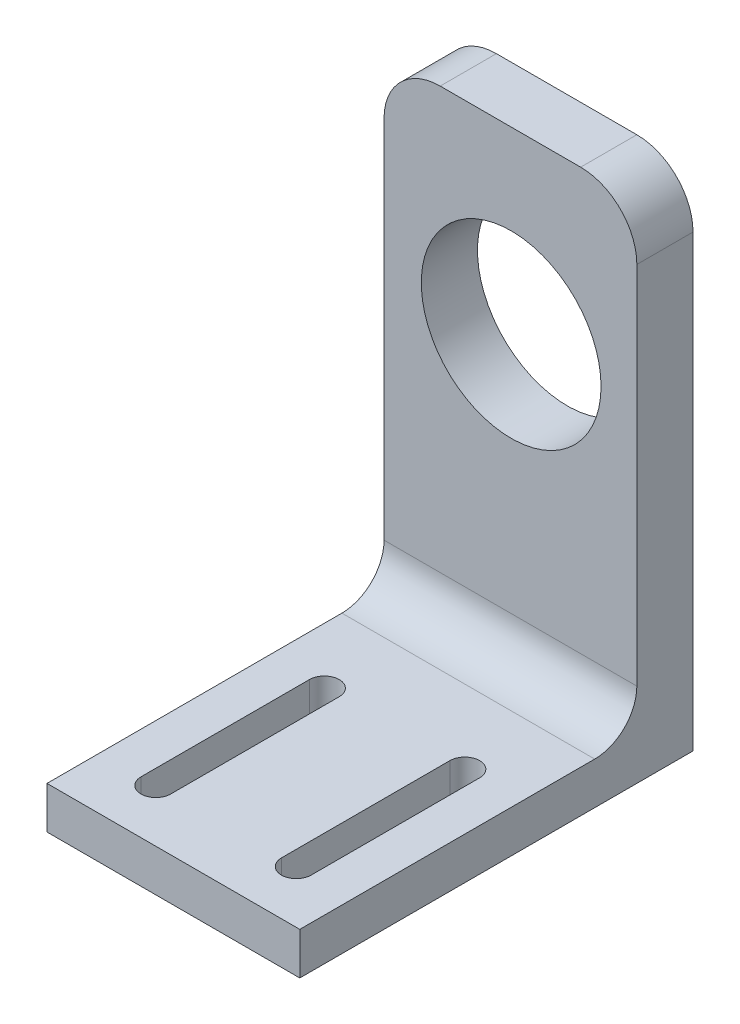
SolidWorks part; units mm, degrees
ref_plane "Front Plane" through (0, 0, 0) normal (0, 0, 1) x (1, 0, 0)
ref_plane "Top Plane" through (0, 0, 0) normal (0, 1, 0) x (1, 0, 0)
ref_plane "Right Plane" through (0, 0, 0) normal (1, 0, 0) x (0, 0, -1)
sketch "Sketch1" plane through (0, 0, 0) normal (0, 0, 1) x (1, 0, 0)
  line L1 (-22.5, 45) -> (22.5, 45)
  line L2 (-22.5, 45) -> (-22.5, -45)
  line L3 (-22.5, -45) -> (22.5, -45)
  line L4 (22.5, 45) -> (22.5, -45)
  line L5 (0, -45) -> (0, 45) construction
  line L6 (-22.5, 0) -> (22.5, 0) construction
  point P0 (0, 0)
  dimension "D1" = 45
  dimension "D2" = 90
extrude "Boss-Extrude1" add sketch "Sketch1" along normal blind 10
sketch "Sketch2" plane through (0, 0, 0) normal (0, 0, 1) x (1, 0, 0)
  circle A0 centre (0.1295, 13.0055) radius 16
extrude "Cut-Extrude1" cut sketch "Sketch2" along normal blind 28
fillet "Fillet1" radius 10 2 edges at (22.5, 45, 5) (-22.5, 45, 5)
sketch "Sketch3" plane through (0, 0, 10) normal (0, 0, 1) x (1, 0, 0)
  line L0 (-22.5, 35) -> (-22.5, -45) construction
  line L1 (-22.5, -37.5) -> (22.5, -37.5)
  line L2 (-22.5, -37.5) -> (-22.5, -45)
  line L3 (-22.5, -45) -> (22.5, -45)
  line L4 (22.5, -37.5) -> (22.5, -45)
  dimension "D1" = 7.5
extrude "Boss-Extrude2" add sketch "Sketch3" along normal blind 60
fillet "Fillet2" radius 7.5 1 edges at (0, -37.5, 10)
sketch "Sketch4" plane through (0, -37.5, 0) normal (0, 1, 0) x (1, 0, 0)
  line L7 (12.5, -30.625) -> (12.5, -60.625) construction
  line L8 (-12.5, -30.625) -> (-12.5, -60.625) construction
  line L9 (-9.85, -30.625) -> (-9.85, -60.625)
  line L10 (-15.15, -30.625) -> (-15.15, -60.625)
  line L11 (9.85, -30.625) -> (9.85, -60.625)
  line L12 (15.15, -30.625) -> (15.15, -60.625)
  arc A0 (-9.85, -30.625) -> (-15.15, -30.625) centre (-12.5, -30.625) ccw
  arc A1 (-15.15, -60.625) -> (-9.85, -60.625) centre (-12.5, -60.625) ccw
  arc A2 (9.85, -30.625) -> (15.15, -30.625) centre (12.5, -30.625) cw
  arc A3 (15.15, -60.625) -> (9.85, -60.625) centre (12.5, -60.625) cw
  point P13 (0, -30.625)
  point P14 (-12.5, -45.625)
  point P21 (12.5, -45.625)
  dimension "D1" = 5.3
  dimension "D2" = 30
extrude "Cut-Extrude2" cut sketch "Sketch4" against normal blind 10
